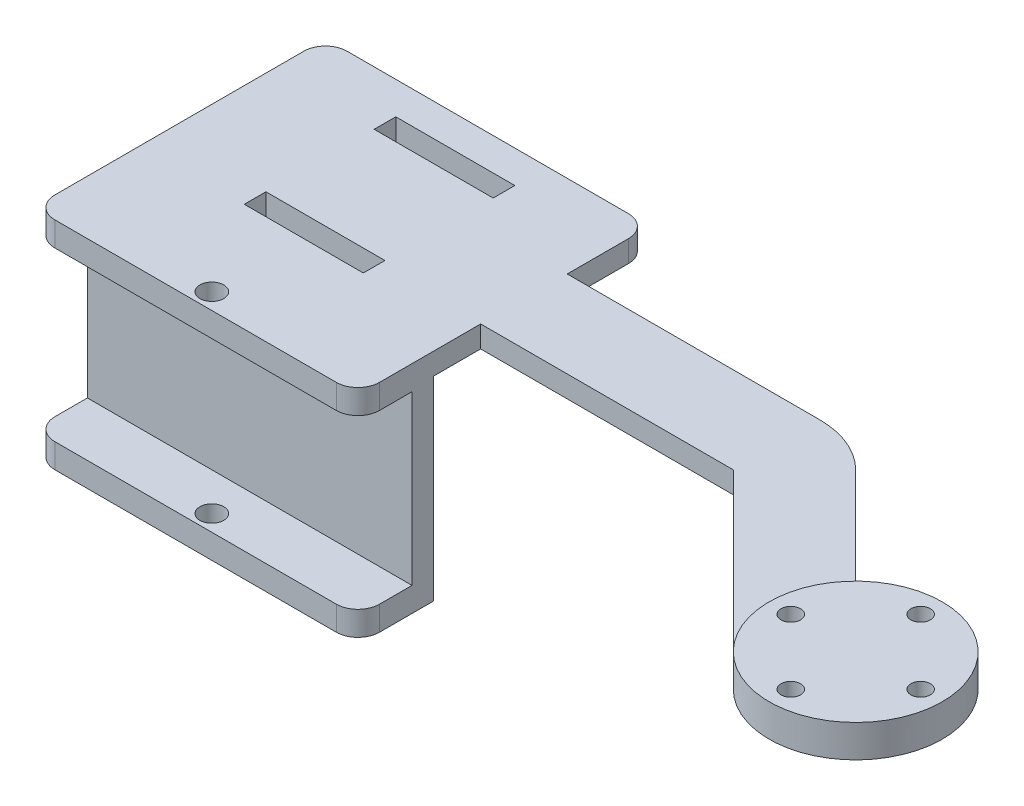
SolidWorks part; units mm, degrees
ref_plane "前视基准面" through (0, 0, 0) normal (0, 0, 1) x (1, 0, 0)
ref_plane "上视基准面" through (0, 0, 0) normal (0, 1, 0) x (1, 0, 0)
ref_plane "右视基准面" through (0, 0, 0) normal (1, 0, 0) x (0, 0, -1)
other "Configuration Table"
sketch "草图1" plane through (0, 0, 0) normal (0, 1, 0) x (1, 0, 0)
  line L1 (0, 0) -> (30, 0)
  line L2 (0, 0) -> (0, -7)
  line L3 (0, -7) -> (30, -7)
  line L4 (30, 0) -> (30, -7)
  dimension "D1" = 7
  dimension "D2" = 30
extrude "凸台-拉伸1" add sketch "草图1" along normal blind 20
sketch "草图2" plane through (0, 0, 7) normal (0, 0, 1) x (1, 0, 0)
  line L0 (0, 20) -> (0, 0) construction
  line L1 (0, 10) -> (6.5085, 10) construction
  line L2 (30, 20) -> (30, 0) construction
  line L3 (0, 17.75) -> (30, 17.75)
  line L4 (0, 17.75) -> (0, 2.25)
  line L5 (0, 2.25) -> (30, 2.25)
  line L6 (30, 17.75) -> (30, 2.25)
  line L7 (0, 17.75) -> (30, 2.25) construction
  point P4 (15, 10)
  point P12 (0, 10)
  dimension "D1" = 15.5
extrude "切除-拉伸1" cut sketch "草图2" against normal blind 5
sketch "草图4" plane through (0, 20, 0) normal (0, 1, 0) x (1, 0, 0)
  line L2 (0, -7) -> (30, -7) construction
  line L3 (30, 0) -> (0, 0) construction
  circle A3 centre (15, -5.5) radius 1.1
  point P0 (15, -7)
  point P1 (15, -5.5)
  dimension "D1" = 5.5
extrude "切除-拉伸2" cut sketch "草图4" against normal through all both and the other way through all
sketch "草图5" plane through (0, 0, 0) normal (0, 0, -1) x (-1, 0, 0)
  line L0 (-30, 20) -> (0, 20) construction
  line L1 (-30, 20) -> (0, 20)
  line L2 (-30, 20) -> (-30, 18)
  line L3 (-30, 18) -> (0, 18)
  line L4 (0, 20) -> (0, 18)
  line L5 (-30, 20) -> (-30, 0) construction
  line L6 (0, 20) -> (0, 0) construction
  dimension "D1" = 2
extrude "凸台-拉伸2" add sketch "草图5" along normal blind 20
sketch "草图6" plane through (0, 20, 0) normal (0, 1, 0) x (1, 0, 0)
  line L0 (0, 10) -> (30, 10) construction
  line L1 (0, 20) -> (0, -7) construction
  line L2 (30, -7) -> (30, 20) construction
  line L3 (0, 20) -> (30, 20) construction
  line L5 (9.5, 17) -> (20.5, 17)
  line L6 (9.5, 17) -> (9.5, 15)
  line L7 (9.5, 15) -> (20.5, 15)
  line L8 (20.5, 17) -> (20.5, 15)
  line L9 (9.5, 17) -> (20.5, 15) construction
  line L10 (9.5, 15) -> (20.5, 17) construction
  line L11 (9.5, 5) -> (20.5, 5)
  line L12 (9.5, 5) -> (9.5, 3)
  line L13 (9.5, 3) -> (20.5, 3)
  line L14 (20.5, 5) -> (20.5, 3)
  line L15 (9.5, 5) -> (20.5, 3) construction
  line L16 (9.5, 3) -> (20.5, 5) construction
  point P8 (15, 16)
  point P9 (15, 4)
  point P10 (15, 16)
  point P15 (15, 4)
  dimension "D1" = 10
  dimension "D2" = 6
  dimension "D3" = 6
  dimension "D4" = 2
  dimension "D5" = 11
  dimension "D6" = 11
  dimension "D7" = 2
extrude "切除-拉伸3" cut sketch "草图6" against normal up to surface (2 mm away) up to face at (15, 18, -10)
sketch "草图7" plane through (0, 18, 0) normal (0, -1, 0) x (1, 0, 0)
  line L0 (0, -20) -> (0, 0) construction
  line L1 (0, -10) -> (0, -12.3431)
  line L2 (0, -10) -> (0, -4.3431)
  line L3 (0, -10) -> (-29, -10) construction
  line L4 (-29, -10) -> (-44.5, -10) construction
  line L5 (-29, -10) -> (-23.3431, -4.3431) construction
  line L6 (0, -12.3431) -> (-23.3431, -12.3431)
  line L7 (0, -12.3431) -> (0, -4.3431)
  line L8 (0, -4.3431) -> (-23.3431, -4.3431)
  line L9 (-23.3431, -12.3431) -> (-23.3431, -4.3431) construction
  line L10 (-44.5, -10) -> (-44.5, 11.6178) construction
  line L11 (-23.3431, -4.3431) -> (-29, -10) construction
  line L12 (-23.3431, -4.3431) -> (-38.9075, 11.2212)
  line L13 (-29, -10) -> (-44.5644, 5.5644)
  line L14 (-38.9075, 11.2212) -> (-44.5644, 5.5644)
  line L15 (15, -20) -> (15, -5) construction
  line L18 (30, -10) -> (30, -12.3431)
  line L19 (30, -10) -> (30, -4.3431)
  line L20 (53.3431, -4.3431) -> (59, -10) construction
  line L21 (74.5, -10) -> (74.5, 11.6178) construction
  line L22 (53.3431, -12.3431) -> (53.3431, -4.3431) construction
  line L23 (59, -10) -> (53.3431, -4.3431) construction
  line L24 (59, -10) -> (74.5, -10) construction
  line L25 (30, -10) -> (59, -10) construction
  line L26 (68.9075, 11.2212) -> (74.5644, 5.5644)
  line L27 (59, -10) -> (74.5644, 5.5644)
  line L28 (53.3431, -4.3431) -> (68.9075, 11.2212)
  line L29 (30, -4.3431) -> (53.3431, -4.3431)
  line L30 (30, -12.3431) -> (53.3431, -12.3431)
  arc A0 (-29, -10) -> (-23.3431, -12.3431) centre (-23.3431, -4.3431) ccw
  arc A1 (59, -10) -> (53.3431, -12.3431) centre (53.3431, -4.3431) cw
  point P0 (0, -10)
  line M12 (30, -20) -> (30, 0)
  dimension "D2" = 29
  dimension "D1" = 8
  dimension "D3" = 45
  dimension "D4" = 15.5
extrude "凸台-拉伸3" add sketch "草图7" against normal up to surface (2 mm away) contours A1 L27 L26 L28 L29 L30 M12 up to face at (15, 20, -16)
sketch "草图9" plane through (0, 18, 0) normal (0, -1, 0) x (1, 0, 0)
  circle A0 centre (74.5644, 5.5644) radius 8
extrude "凸台-拉伸4" add sketch "草图9" against normal blind 3
sketch "草图10" plane through (0, 21, 0) normal (0, 1, 0) x (1, 0, 0)
  circle A0 centre (74.5644, -5.5644) radius 6 construction
  circle A1 centre (74.5644, -5.5644) radius 8 construction
  circle A2 centre (68.5644, -5.5644) radius 0.9
  circle A3 centre (74.5644, 0.4356) radius 0.9
  circle A4 centre (80.5644, -5.5644) radius 0.9
  circle A5 centre (74.5644, -11.5644) radius 0.9
extrude "切除-拉伸4" cut sketch "草图10" against normal up to next
fillet "圆角1" radius 2 6 edges at (30, 1.125, 7) (0, 1.125, 7) (30, 19, -20) (0, 19, -20) (30, 18.875, 7) (0, 18.875, 7)
sketch "草图11" plane through (0, 21, 0) normal (0, 1, 0) x (1, 0, 0)
  point P0 (74.5644, -5.5644)
